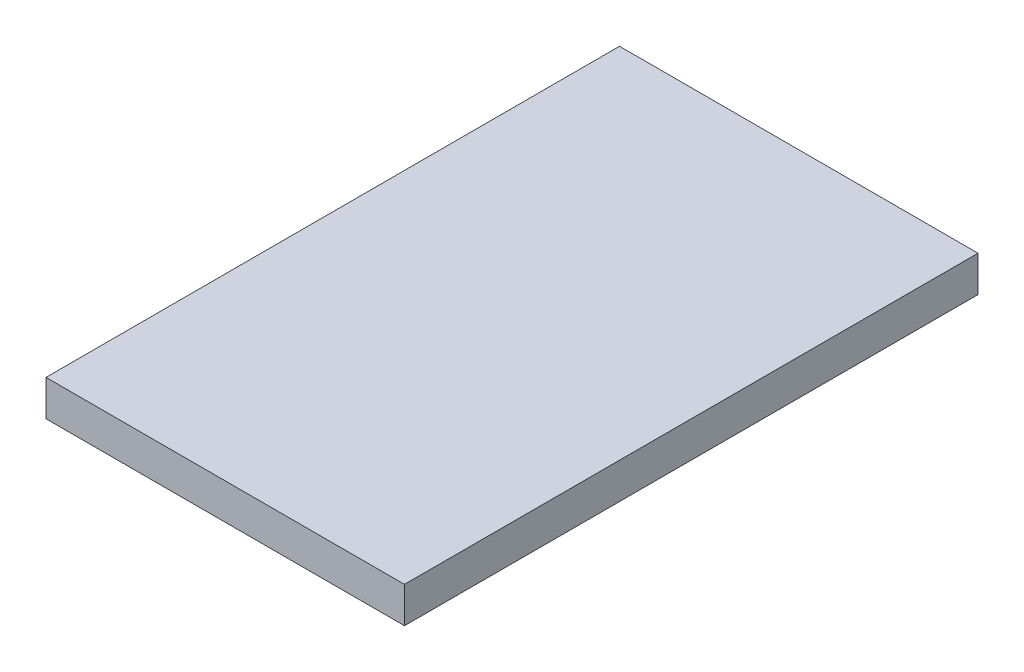
SolidWorks part; units mm, degrees
material "6061-T6 (SS)"
ref_plane "Front Plane" through (0, 0, 0) normal (0, 0, 1) x (1, 0, 0)
ref_plane "Top Plane" through (0, 0, 0) normal (0, 1, 0) x (1, 0, 0)
ref_plane "Right Plane" through (0, 0, 0) normal (1, 0, 0) x (0, 0, -1)
sketch "Sketch1" plane through (0, 0, 0) normal (0, 0, 1) x (1, 0, 0)
  line L0 (0, 0) -> (50, 0)
  line L1 (0, 0) -> (0, 5)
  line L2 (0, 5) -> (50, 5)
  line L3 (50, 5) -> (50, 0)
extrude "Boss-Extrude1" add sketch "Sketch1" along normal blind 80
